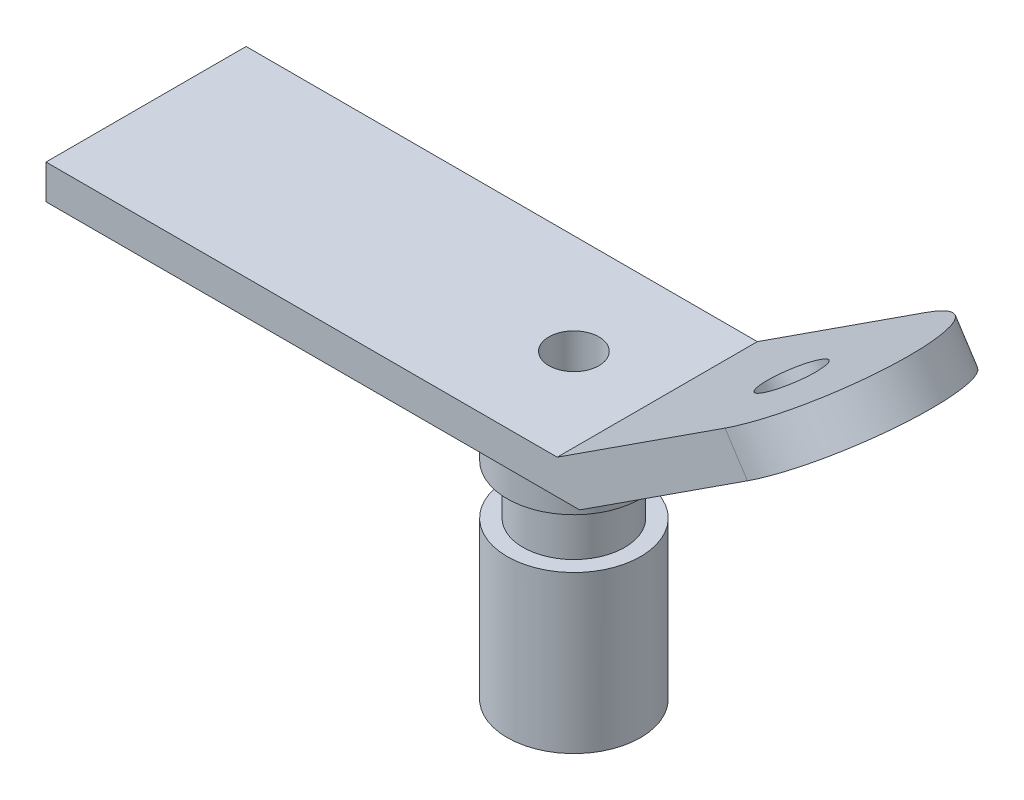
SolidWorks part; units mm, degrees
material "Custom Plastic"
ref_plane "Front Plane" through (0, 0, 0) normal (0, 0, 1) x (1, 0, 0)
ref_plane "Top Plane" through (0, 0, 0) normal (0, 1, 0) x (1, 0, 0)
ref_plane "Right Plane" through (0, 0, 0) normal (1, 0, 0) x (0, 0, -1)
other "Configuration Table"
sketch "Sketch1" plane through (0, 0, 0) normal (0, 0, 1) x (1, 0, 0)
  line L0 (0, 0) -> (127.7788, 83.0562)
  line L1 (127.7788, 83.0562) -> (119.2464, 96.1831)
  line L2 (119.2464, 96.1831) -> (-8.5324, 13.1268)
  line L3 (-8.5324, 13.1268) -> (0, 0)
  line L4 (0, 0) -> (-203.2, 0)
  line L5 (-203.2, 0) -> (-203.2, 13.1268)
  line L6 (-203.2, 13.1268) -> (-8.5324, 13.1268)
  dimension "D1" = 203.2
  dimension "D2" = 152.4
extrude "Boss-Extrude1" add sketch "Sketch1" along normal blind 76.2 contours L6 L5 L4 L3 | L2 L3 L0 L1
sketch "Sketch2" plane through (0, 0, 0) normal (0, -1, 0) x (1, 0, 0)
  line L0 (-14.8824, 76.2) -> (-14.8824, 0) construction
  line L1 (0, 76.2) -> (0, 0) construction
  line L2 (0, 0) -> (-203.2, 0) construction
  line L3 (0, 76.2) -> (-203.2, 76.2) construction
  line L4 (-203.2, 38.1) -> (134.5551, 38.1) construction
  line L5 (-203.2, 76.2) -> (-203.2, 0) construction
  line L6 (-8.5324, 76.2) -> (-8.5324, 0) construction
  circle A0 centre (-40.2824, 38.1) radius 25.4
  circle A1 centre (-40.2824, 38.1) radius 9.525
  point P7 (0, 38.1)
  dimension "D2" = 19.05
  dimension "D3" = 50.8
  dimension "D1" = 38.1
  dimension "D4" = 6.35
extrude "Boss-Extrude2" add sketch "Sketch2" along normal blind 101.6
ref_plane "Plane1" through (0, 0, 38.1) normal (0, 0, 1) x (1, 0, 0)
sketch "Sketch4" plane through (0, 0, 38.1) normal (0, 0, 1) x (1, 0, 0)
  line L0 (-65.6824, -101.6) -> (-14.8824, -101.6) construction
  line L1 (-65.9926, -22.8346) -> (-59.6426, -22.8346)
  line L2 (-65.9926, -22.8346) -> (-65.9926, -41.8846)
  line L3 (-65.9926, -41.8846) -> (-59.6426, -41.8846)
  line L4 (-59.6426, -22.8346) -> (-59.6426, -41.8846)
  line L5 (-40.2824, -101.6) -> (-40.2824, 26.8641) construction
  dimension "D1" = 78.7654
  dimension "D2" = 6.35
  dimension "D3" = 19.05
revolve "Cut-Revolve1" cut sketch "Sketch4" angle 360 about L5
sketch "Sketch5" plane through (0, 0, 0) normal (0, -1, 0) x (1, 0, 0)
  circle A0 centre (-40.2824, 38.1) radius 9.525 construction
  circle A1 centre (-40.2824, 38.1) radius 9.525
extrude "Cut-Extrude1" cut sketch "Sketch5" against normal through all
sketch "Sketch7" plane through (-8.5324, 13.1268, 0) normal (-0.545, 0.8384, 0) x (0.8384, 0.545, 0)
  line L0 (0, -38.1) -> (187.0308, -38.1) construction
  line L1 (0, -76.2) -> (0, 0) construction
  circle A0 centre (61.0108, -38.1) radius 57.15 construction
  circle A1 centre (61.0108, -38.1) radius 10.9982
  dimension "D1" = 114.3
  dimension "D3" = 21.9964
  dimension "D2" = 61.0108
extrude "Cut-Extrude2" cut sketch "Sketch7" against normal through all
sketch "Sketch8" plane through (-8.5324, 13.1268, 0) normal (-0.545, 0.8384, 0) x (0.8384, 0.545, 0)
  line L1 (152.4, 0) -> (0, 0) construction
  line L3 (152.4, -76.2) -> (0, -76.2) construction
  line L4 (76.2, 0) -> (152.4, 0)
  line L5 (152.4, 0) -> (152.4, -76.2)
  line L6 (152.4, -76.2) -> (76.2, -76.2)
  line L7 (0, -76.2) -> (0, 0) construction
  arc A0 (76.2, 0) -> (76.2, -76.2) centre (76.2, -38.1) cw
  dimension "D1" = 38.1
  dimension "D2" = 76.2
extrude "Cut-Extrude3" cut sketch "Sketch8" against normal through all
